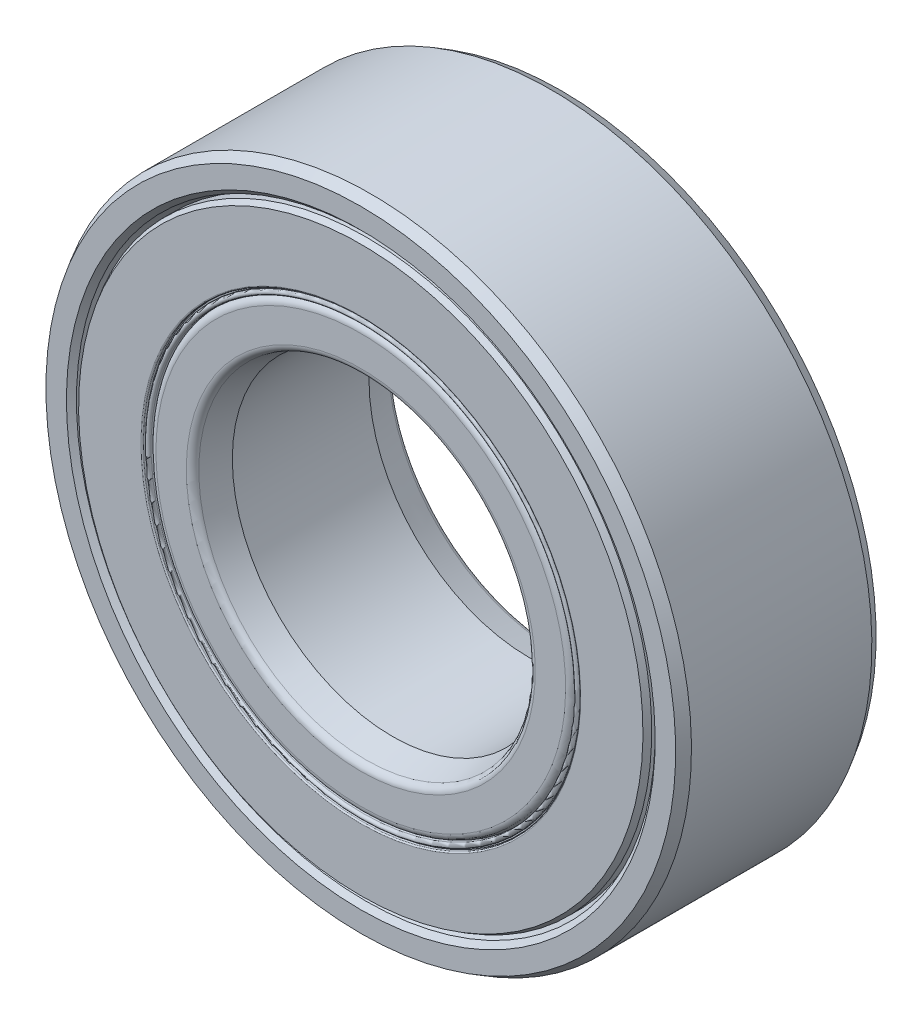
SolidWorks part; units mm, degrees
ref_plane "Front Plane" through (0, 0, 0) normal (0, 0, 1) x (1, 0, 0)
ref_plane "Top Plane" through (0, 0, 0) normal (0, 1, 0) x (1, 0, 0)
ref_plane "Right Plane" through (0, 0, 0) normal (1, 0, 0) x (0, 0, -1)
sketch "Sketch1" plane through (0, 0, 0) normal (0, 0, 1) x (1, 0, 0)
  line L0 (-8, 0) -> (8, 0) construction
  line L1 (-4, 0) -> (4, 0) construction
  circle A0 centre (0, 0) radius 4 construction
  circle A1 centre (0, 0) radius 8 construction
  point P3 (0, 0)
  point P6 (0, 0)
  point P7 (0, -4)
  point P11 (0, -8)
  point P12 (0, 4)
  point P13 (0, 8)
  dimension "OD" = 16
  dimension "ID" = 8
sketch "Sketch2" plane through (0, 0, 0) normal (1, 0, 0) x (0, 0, -1)
  line L0 (-2.5, 8) -> (2.5, 8) construction
  line L1 (0, 8) -> (0, -8) construction
  line L2 (2.25, 8) -> (-2.25, 8)
  line L3 (-2.25, 8) -> (-2.5, 7.8557)
  line L4 (-2.5, 7.8557) -> (-2.5, 7.3437)
  line L5 (-2.1037, 7.12) -> (-1.1899, 7.12)
  line L6 (2.1037, 7.12) -> (1.1899, 7.12)
  line L7 (2.5, 7.8557) -> (2.5, 7.3437)
  line L8 (2.25, 8) -> (2.5, 7.8557)
  line L9 (-1.1899, 7.12) -> (-1.1899, 7.4133) construction
  line L10 (-1.1899, 7.4133) -> (-1.1899, 7.7067) construction
  line L11 (0, 8) -> (0, -8) construction
  line L12 (-2.5, 0) -> (2.5, 0) construction
  line L13 (2.5, 4) -> (-2.5, 4) construction
  line L14 (-2.5, 4) -> (-2.5, -4) construction
  line L15 (-2.5, -4) -> (2.5, -4) construction
  line L16 (2.5, 8) -> (2.5, -8) construction
  line L17 (-1.1899, 7.7067) -> (-1.1899, 8) construction
  line L18 (-1.1899, 7.7067) -> (0, 7.7067) construction
  line L20 (-2.1037, 7.12) -> (-2.375, 7.2187)
  line L21 (-2.375, 7.2187) -> (-2.5, 7.3437)
  line L26 (2.375, 7.2187) -> (2.5, 7.3437)
  line L27 (2.1037, 7.12) -> (2.375, 7.2187)
  arc A0 (-1.1899, 7.12) -> (1.1899, 7.12) centre (0, 6.2067) cw
  circle A1 centre (0, 6.2067) radius 1.5 construction
  point P17 (0, 0)
  point P21 (0, 8)
  point P30 (0, -4)
  dimension "Approx. Ball Dia." = 3
  dimension "Width" = 5
  dimension "For Shaft Diameter" = 8
  dimension "For Housing ID" = 16
  dimension "D4" = 14.24
  dimension "D2" = 20
  dimension "D5" = 45
  dimension "D1" = 30
  dimension "D6" = 0.25
  dimension "D7" = 0.125
sketch "Sketch3" plane through (0, 0, 0) normal (1, 0, 0) x (0, 0, -1)
  line L14 (-2.1037, 7.12) -> (-2.375, 7.2187) construction
  line L15 (-2.375, 7.2187) -> (-2.5, 7.3437) construction
  line L16 (-2.5, 7.8557) -> (-2.5, 7.3437) construction
  line L17 (-2.25, 8) -> (-2.5, 7.8557) construction
  line L18 (2.25, 8) -> (-2.25, 8) construction
  line L19 (2.25, 8) -> (2.5, 7.8557) construction
  line L20 (2.5, 7.8557) -> (2.5, 7.3437) construction
  line L21 (2.375, 7.2187) -> (2.5, 7.3437) construction
  line L22 (2.1037, 7.12) -> (2.375, 7.2187) construction
  line L23 (2.1037, 7.12) -> (1.1899, 7.12) construction
  line L24 (-2.1037, 7.12) -> (-1.1899, 7.12) construction
  line L25 (-2.1037, 7.12) -> (-2.375, 7.2187)
  line L26 (-2.375, 7.2187) -> (-2.5, 7.3437)
  line L27 (-2.5, 7.8557) -> (-2.5, 7.3437)
  line L28 (-2.25, 8) -> (-2.5, 7.8557)
  line L29 (2.25, 8) -> (-2.25, 8)
  line L30 (2.25, 8) -> (2.5, 7.8557)
  line L31 (2.5, 7.8557) -> (2.5, 7.3437)
  line L32 (2.375, 7.2187) -> (2.5, 7.3437)
  line L33 (2.1037, 7.12) -> (2.375, 7.2187)
  line L34 (2.1037, 7.12) -> (1.1899, 7.12)
  line L35 (-2.1037, 7.12) -> (-1.1899, 7.12)
  arc A2 (1.1899, 7.12) -> (-1.1899, 7.12) centre (0, 6.2067) ccw construction
  arc A3 (1.1899, 7.12) -> (-1.1899, 7.12) centre (0, 6.2067) ccw
revolve "Revolve1" add sketch "Sketch3" angle 360 about L12
sketch "Sketch4" plane through (0, 0, 0) normal (1, 0, 0) x (0, 0, -1)
  line L0 (0, 8) -> (0, -8) construction
  line L1 (0, 8) -> (0, -8) construction
  line L2 (-1.7051, 4) -> (-2.3644, 4.1767)
  line L3 (-2.5, 4.3533) -> (-2.5, 5.1104)
  line L4 (2.5, -7.8557) -> (2.5, 7.8557) construction
  line L5 (-2.3171, 5.2933) -> (-1.1899, 5.2933)
  line L6 (-1.7051, 4) -> (1.7051, 4)
  line L7 (2.5, 7.8557) -> (2.5, 7.3437) construction
  line L8 (1.7051, 4) -> (2.3644, 4.1767)
  line L9 (0, 7.7067) -> (0, 4) construction
  line L10 (2.5, 4.3533) -> (2.5, 5.1104)
  line L11 (2.3171, 5.2933) -> (1.1899, 5.2933)
  line L12 (1.7051, 4) -> (1.7051, 4.1767) construction
  line L13 (1.7051, 4.1767) -> (1.7051, 4.3533) construction
  line L14 (1.7051, 4.3533) -> (1.7051, 4.53) construction
  line L15 (1.7051, 4.53) -> (1.7051, 4.7067) construction
  circle A0 centre (0, 6.2067) radius 1.5 construction
  arc A1 (1.1899, 5.2933) -> (-1.1899, 5.2933) centre (0, 6.2067) cw
  arc A2 (2.5, 5.1104) -> (2.3171, 5.2933) centre (2.3171, 5.1104) ccw
  arc A3 (-2.5, 5.1104) -> (-2.3171, 5.2933) centre (-2.3171, 5.1104) cw
  arc A4 (2.3644, 4.1767) -> (2.5, 4.3533) centre (2.3171, 4.3533) ccw
  arc A5 (-2.3644, 4.1767) -> (-2.5, 4.3533) centre (-2.3171, 4.3533) cw
  point P14 (2.5, 4.213)
  point P36 (0, 4.7067)
  dimension "D1" = 15
revolve "Revolve2" add sketch "Sketch4" angle 360 about L12
sketch "Sketch5" plane through (0, 0, 0) normal (1, 0, 0) x (0, 0, -1)
  line L0 (-1.5, 6.2067) -> (1.5, 6.2067)
  arc A2 (-1.5, 6.2067) -> (1.5, 6.2067) centre (0, 6.2067) cw
  arc A3 (1.1899, 7.12) -> (-1.1899, 7.12) centre (0, 6.2067) ccw construction
revolve "Revolve3" add sketch "Sketch5" angle 360 about L0
pattern_circular "CirPattern1" count 9 over 360 about axis through (0, 0, 0) along (0, 0, 1) of bodies 104
sketch "Sketch6" plane through (0, 0, 0) normal (1, 0, 0) x (0, 0, -1)
  line L1 (-2.3614, 7.12) -> (-1.5, 7.12)
  line L2 (-2.5, 7.04) -> (-2.5, 5.4853)
  line L3 (-2.468, 5.4533) -> (-1.5, 5.4533)
  line L4 (-1.5, 7.12) -> (-1.5, 5.4533)
  line L5 (-2.5, 4.3533) -> (-2.5, 5.1104) construction
  line L6 (-2.25, 8) -> (-2.5, 7.8557) construction
  line L7 (0, 8) -> (0, 4) construction
  line L8 (2.468, 5.4533) -> (1.5, 5.4533)
  line L9 (1.5, 7.12) -> (1.5, 5.4533)
  line L10 (2.3614, 7.12) -> (1.5, 7.12)
  line L11 (2.5, 7.04) -> (2.5, 5.4853)
  line L13 (-2.3171, 5.2933) -> (-1.1899, 5.2933) construction
  line L14 (-2.5, 7.04) -> (-2.3614, 7.12)
  line L15 (-2.1037, 7.12) -> (-1.1899, 7.12) construction
  line L16 (2.5, 7.04) -> (2.3614, 7.12)
  arc A0 (-2.5, 5.4853) -> (-2.468, 5.4533) centre (-2.468, 5.4853) ccw
  circle A1 centre (0, 6.2067) radius 1.5 construction
  arc A2 (2.5, 5.4853) -> (2.468, 5.4533) centre (2.468, 5.4853) cw
  point P26 (-2.5, 5.4533)
  dimension "D3" = 0.032
  dimension "D1" = 0.16
  dimension "D2" = 0.08
revolve "Revolve4" add sketch "Sketch6" angle 360 about L12
sketch "Sketch7" plane through (0, 0, 0) normal (1, 0, 0) x (0, 0, -1)
  line L3 (-1.5, 5.4533) -> (-2.3785, 5.4533)
  line L4 (-2.468, 5.4533) -> (-1.5, 5.4533) construction
  line L7 (0, 4.7067) -> (0, 4) construction
  line L8 (0, 8) -> (0, -8) construction
  line L21 (-2.3785, 5.4533) -> (-2.4179, 5.4464)
  line L22 (-2.415, 5.4133) -> (-2.44, 5.4133)
  line L23 (-2.44, 5.2933) -> (-1.5, 5.2933)
  line L24 (-1.5, 5.2933) -> (-1.5, 5.4533)
  line L25 (-2.3171, 5.2933) -> (-1.1899, 5.2933) construction
  line L26 (-2.5, 5.4853) -> (-2.5, 5.2933) construction
  line L27 (-2.5, 5.2933) -> (-2.44, 5.2933) construction
  line L28 (-2.3785, 5.4533) -> (-2.3785, 5.4133) construction
  line L29 (-2.3785, 5.4133) -> (-2.3785, 5.3733) construction
  line L30 (-2.3785, 5.3733) -> (-2.3785, 5.3333) construction
  line L31 (-2.3785, 5.3333) -> (-2.3785, 5.2933) construction
  circle A2 centre (0, 6.2067) radius 1.5 construction
  arc A9 (-2.4179, 5.4464) -> (-2.415, 5.4133) centre (-2.415, 5.43) ccw
  arc A10 (-2.44, 5.4133) -> (-2.44, 5.2933) centre (-2.44, 5.3533) ccw
  dimension "D1" = 0.025
  dimension "D2" = 10
revolve "Revolve5" add sketch "Sketch7" angle 360 about L12
equation "\"D4@Sketch2\"=\"OD@Sketch1\"*.89"
equation "\"D1@Sketch6\"=(\"OD@Sketch1\"-\"ID@Sketch1\")*.02"
equation "\"D2@Sketch6\"=\"D1@Sketch6\"*.5"
equation "\"D3@Sketch6\"=\"D1@Sketch6\"*.2"
equation "\"D6@Sketch2\"=\"Width@Sketch2\"*.05"
equation "\"D7@Sketch2\"=\"D6@Sketch2\"*.5"
equation "\"D1@CirPattern1\" =  ( pi * \"OD@Sketch1\" )  * .5625 / \"Approx. Ball Dia.@Sketch2\""
equation "\"Approx. Ball Dia.@Sketch2\"=(\"OD@Sketch1\"-\"ID@Sketch1\")*.5*.75"
